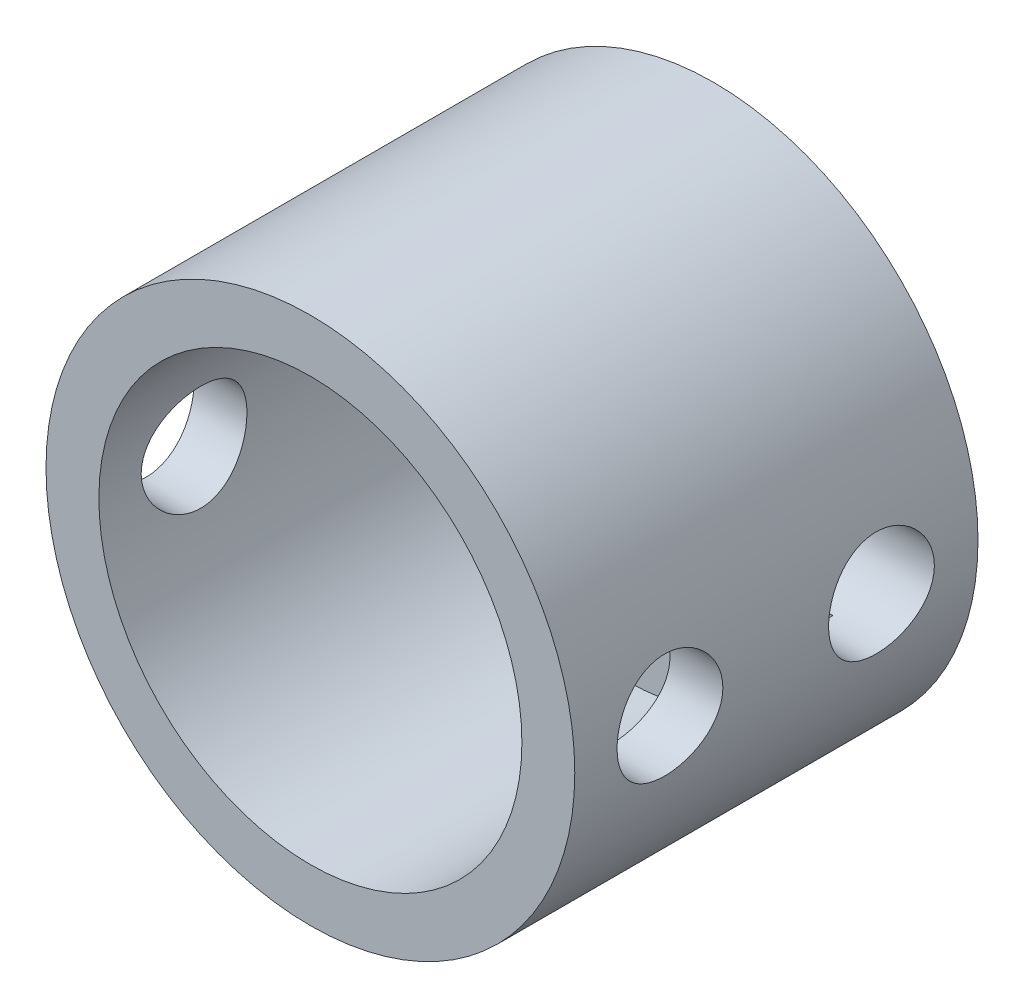
SolidWorks part; units mm, degrees
ref_plane "Plano frontal" through (0, 0, 0) normal (0, 0, 1) x (1, 0, 0)
ref_plane "Plano superior" through (0, 0, 0) normal (0, 1, 0) x (1, 0, 0)
ref_plane "Plano direito" through (0, 0, 0) normal (1, 0, 0) x (0, 0, -1)
sketch "Esboço1" plane through (0, 0, 0) normal (0, 0, 1) x (1, 0, 0)
  circle A0 centre (0, 0) radius 12.5
  dimension "D1" = 25
extrude "Ressalto-extrusão1" add sketch "Esboço1" along normal blind 4.064
sketch "Esboço2" plane through (0, 0, 4.064) normal (0, 0, 1) x (1, 0, 0)
  circle A0 centre (0, 0) radius 12.5
  circle A1 centre (0, 0) radius 10
  dimension "D1" = 20
  dimension "D2" = 25
extrude "Ressalto-extrusão2" add sketch "Esboço2" along normal blind 15
sketch "Esboço3" plane through (0, 0, 0) normal (1, 0, 0) x (0, 0, -1)
  line L3 (-19.064, 12.5) -> (-19.064, -12.5) construction
  circle A0 centre (-14.564, 0) radius 2.5
  circle A1 centre (-4.564, 0) radius 2.5
  dimension "D1" = 5
  dimension "D2" = 5
  dimension "D4" = 4.5
  dimension "D3" = 10
extrude "Corte-extrusão1" cut sketch "Esboço3" against normal blind 23 and the other way blind 24
